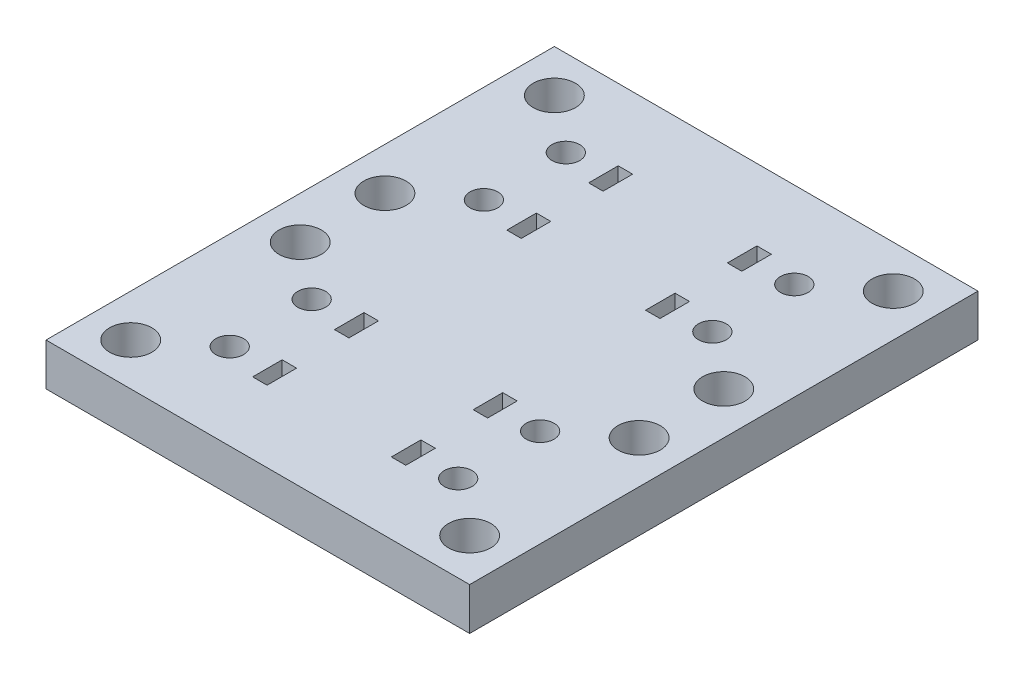
SolidWorks part; units mm, degrees
ref_plane "Front Plane" through (0, 0, 0) normal (0, 0, 1) x (1, 0, 0)
ref_plane "Top Plane" through (0, 0, 0) normal (0, 1, 0) x (1, 0, 0)
ref_plane "Right Plane" through (0, 0, 0) normal (1, 0, 0) x (0, 0, -1)
sketch "Sketch1" plane through (0, 0, 0) normal (0, 1, 0) x (1, 0, 0)
  line L0 (0, 76.2) -> (0, 0) construction
  line L1 (0, 76.2) -> (127, 76.2)
  line L2 (-101.6, -50.8) -> (101.6, -50.8) construction
  line L3 (0, 0) -> (-38.2832, 0) construction
  line L4 (127, 76.2) -> (127, 0)
  line L5 (-127, -76.2) -> (127, -76.2) construction
  line L6 (101.6, 50.8) -> (101.6, 0) construction
  line L7 (0, 0) -> (0, -31.6036) construction
  line L8 (101.6, 50.8) -> (127, 50.8) construction
  line L9 (0, 0) -> (127, 0)
  line L10 (0, 0) -> (0, 76.2)
  line L11 (-127, 76.2) -> (127, 76.2) construction
  line L12 (0, 50.8) -> (101.6, 50.8) construction
  line L13 (-101.6, 50.8) -> (101.6, 50.8) construction
  line L14 (101.6, 50.8) -> (101.6, 76.2) construction
  line L15 (-101.6, 50.8) -> (-101.6, -50.8) construction
  line L16 (-127, 76.2) -> (-127, -76.2) construction
  line L17 (101.6, 50.8) -> (101.6, -50.8) construction
  line L18 (127, 76.2) -> (127, -76.2) construction
  line L20 (37.2556, 33.3917) -> (45.9154, 33.3917)
  line L21 (37.2556, 33.3917) -> (37.2556, 15.6797)
  line L22 (37.2556, 15.6797) -> (45.9154, 15.6797)
  line L23 (45.9154, 33.3917) -> (45.9154, 15.6797)
  circle A0 centre (68.4916, 24.5688) radius 8.3302
  circle A1 centre (101.6, 50.8) radius 12.7
  dimension "D3" = 25.4
  dimension "D4" = 25.4
  dimension "D1" = 152.4
  dimension "D2" = 254
extrude "Boss-Extrude1" add sketch "Sketch1" along normal blind 25.4
mirror "Mirror1" about plane through (0, 25.4, 0) normal (1, 0, 0) of bodies 101
mirror "Mirror2" about plane through (0, 25.4, 0) normal (0, 0, -1) of bodies 102
mirror "Mirror3"
